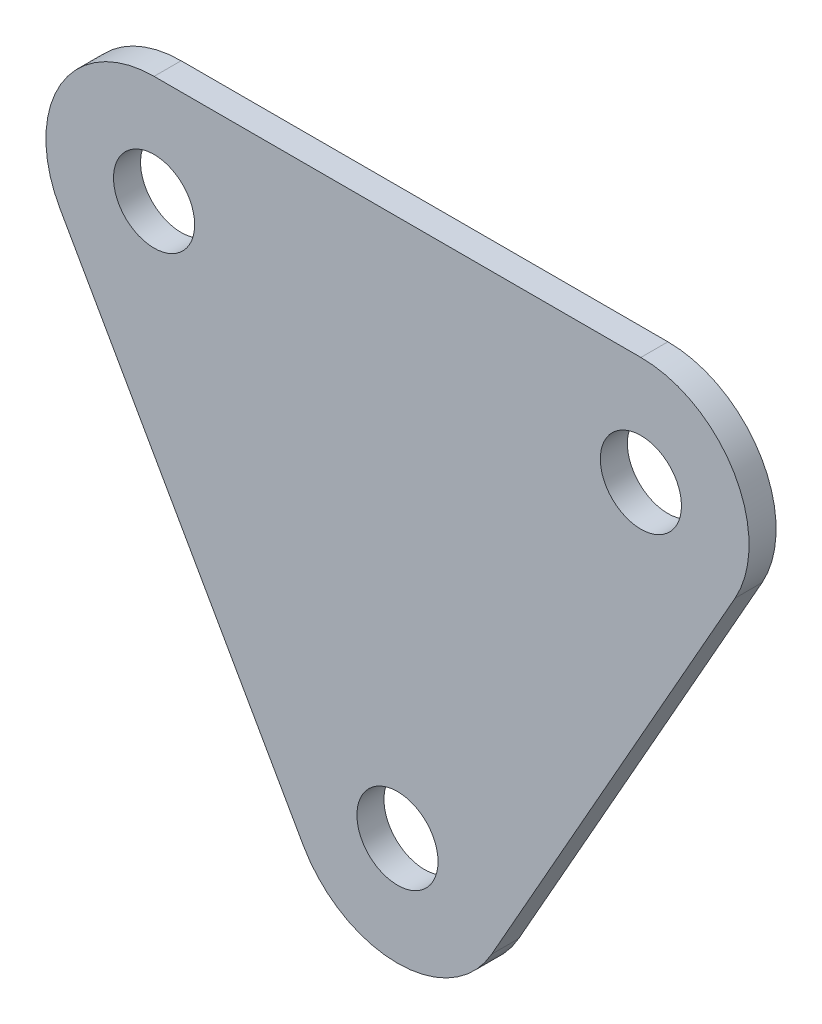
SolidWorks part; units mm, degrees
ref_plane "Front Plane" through (0, 0, 0) normal (0, 0, 1) x (1, 0, 0)
ref_plane "Top Plane" through (0, 0, 0) normal (0, 1, 0) x (1, 0, 0)
ref_plane "Right Plane" through (0, 0, 0) normal (1, 0, 0) x (0, 0, -1)
sketch "Sketch2" plane through (0, 0, 0) normal (0, 0, 1) x (1, 0, 0)
  line L0 (0, 0) -> (360, 0) construction
  line L1 (180, 0) -> (180, -318) construction
  line L2 (110.3795, -357.4079) -> (-69.6205, -39.4079)
  line L3 (249.6205, -357.4079) -> (429.6205, -39.4079)
  line L4 (0, 80) -> (360, 80)
  circle A0 centre (0, 0) radius 30
  arc A1 (0, 80) -> (-69.6205, -39.4079) centre (0, 0) ccw
  circle A2 centre (360, 0) radius 30
  arc A3 (429.6205, -39.4079) -> (360, 80) centre (360, 0) ccw
  circle A4 centre (180, -318) radius 30
  arc A5 (110.3795, -357.4079) -> (249.6205, -357.4079) centre (180, -318) ccw
  dimension "D1" = 60
  dimension "60" = 60
  dimension "D2" = 160
  dimension "D3" = 160
  dimension "D5" = 180
  dimension "D7" = 60
  dimension "D8" = 160
  dimension "D4" = 360
  dimension "D6" = 318
extrude "Boss-Extrude1" add sketch "Sketch2" along normal blind 20
